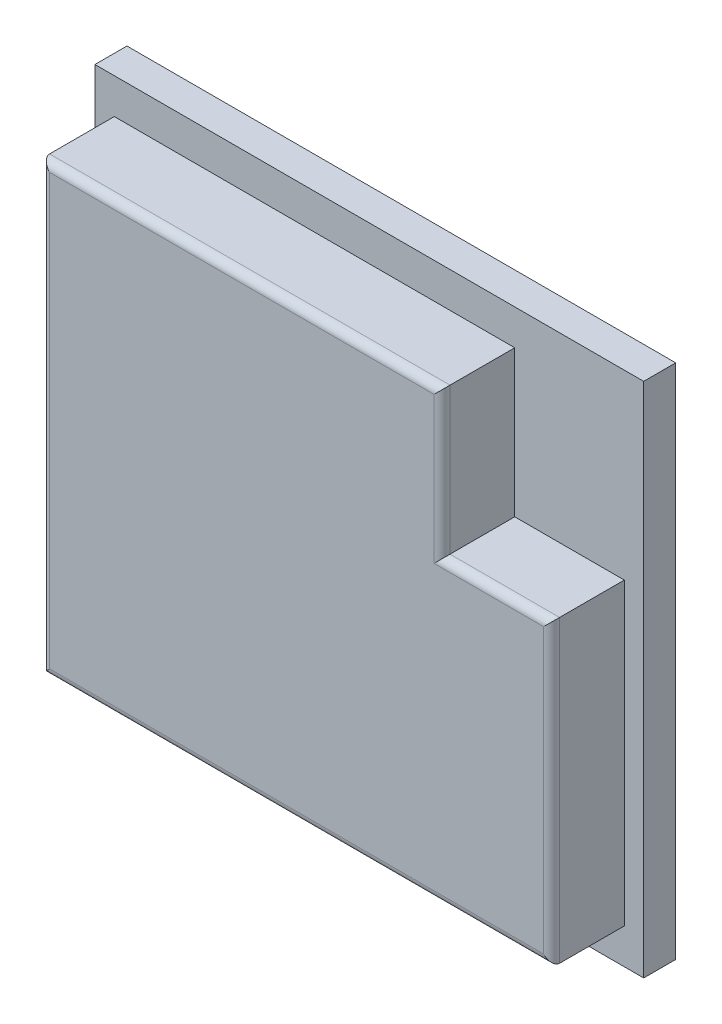
SolidWorks part; units mm, degrees
ref_plane "Спереди" through (0, 0, 0) normal (0, 0, 1) x (1, 0, 0)
ref_plane "Сверху" through (0, 0, 0) normal (0, 1, 0) x (1, 0, 0)
ref_plane "Справа" through (0, 0, 0) normal (1, 0, 0) x (0, 0, -1)
sketch "Эскиз1" plane through (0, 0, 0) normal (0, 0, 1) x (1, 0, 0)
  line L1 (-8.565, -8.065) -> (8.565, -8.065)
  line L2 (-8.565, -8.065) -> (-8.565, 8.065)
  line L3 (-8.565, 8.065) -> (8.565, 8.065)
  line L4 (8.565, -8.065) -> (8.565, 8.065)
  line L5 (-8.565, -8.065) -> (8.565, 8.065) construction
  line L6 (-8.565, 8.065) -> (8.565, -8.065) construction
  point P0 (0, 0)
  dimension "D1" = 17.13
  dimension "D2" = 16.13
extrude "Бобышка-Вытянуть1" add sketch "Эскиз1" along normal blind 1
sketch "Эскиз2" plane through (0, 0, 1) normal (0, 0, 1) x (1, 0, 0)
  line L0 (4.54, 6.96) -> (4.54, 2.39)
  line L1 (-7.96, -6.96) -> (7.96, -6.96)
  line L2 (-7.96, -6.96) -> (-7.96, 6.96)
  line L3 (-7.96, 6.96) -> (4.54, 6.96)
  line L4 (7.96, -6.96) -> (7.96, 2.39)
  line L5 (-7.96, -6.96) -> (7.96, 6.96) construction
  line L6 (-7.96, 6.96) -> (7.96, -6.96) construction
  line L7 (4.54, 2.39) -> (7.96, 2.39)
  point P0 (0, 0)
  dimension "D1" = 15.92
  dimension "D2" = 13.92
  dimension "D3" = 9.35
  dimension "D4" = 12.5
extrude "Бобышка-Вытянуть2" add sketch "Эскиз2" along normal blind 2.27
fillet "Скругление1" radius 0.25 6 edges at (-1.71, 6.96, 3.27) (4.54, 4.675, 3.27) (6.25, 2.39, 3.27) (7.96, -2.285, 3.27) (0, -6.96, 3.27) (-7.96, 0, 3.27)
